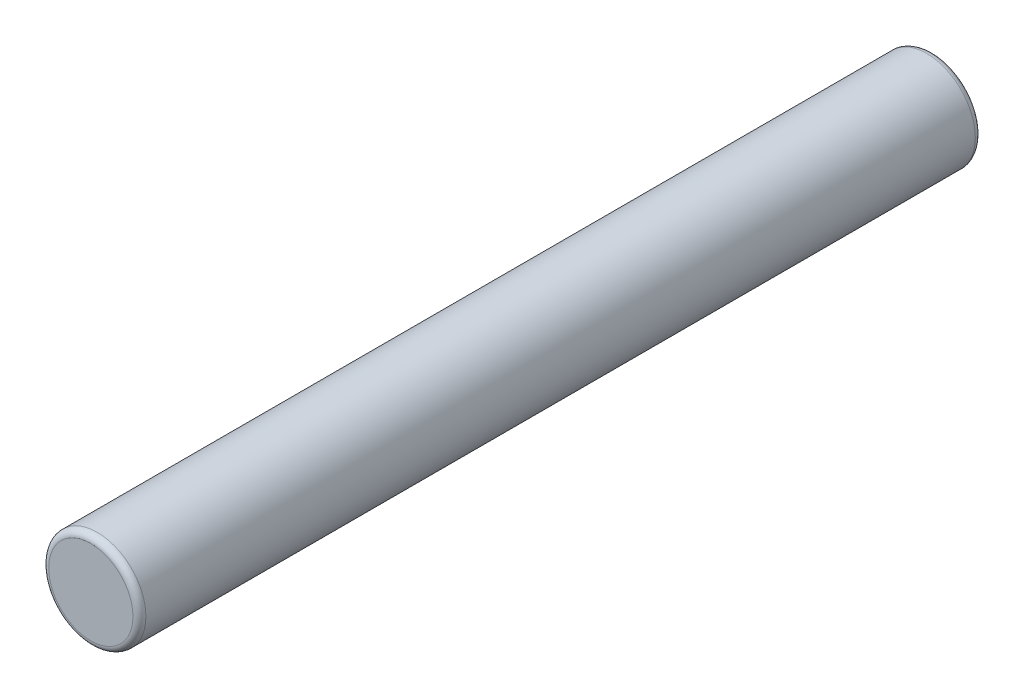
SolidWorks part; units mm, degrees
ref_plane "Front Plane" through (0, 0, 0) normal (0, 0, 1) x (1, 0, 0)
ref_plane "Top Plane" through (0, 0, 0) normal (0, 1, 0) x (1, 0, 0)
ref_plane "Right Plane" through (0, 0, 0) normal (1, 0, 0) x (0, 0, -1)
sketch "Sketch1" plane through (0, 0, 0) normal (0, 0, 1) x (1, 0, 0)
  circle A0 centre (0, 0) radius 1.5
  dimension "D1" = 3
extrude "Boss-Extrude1" add sketch "Sketch1" along normal blind 26
fillet "Fillet1" radius 0.2 2 edges at (1.5, 0, 0) (1.5, 0, 26)
